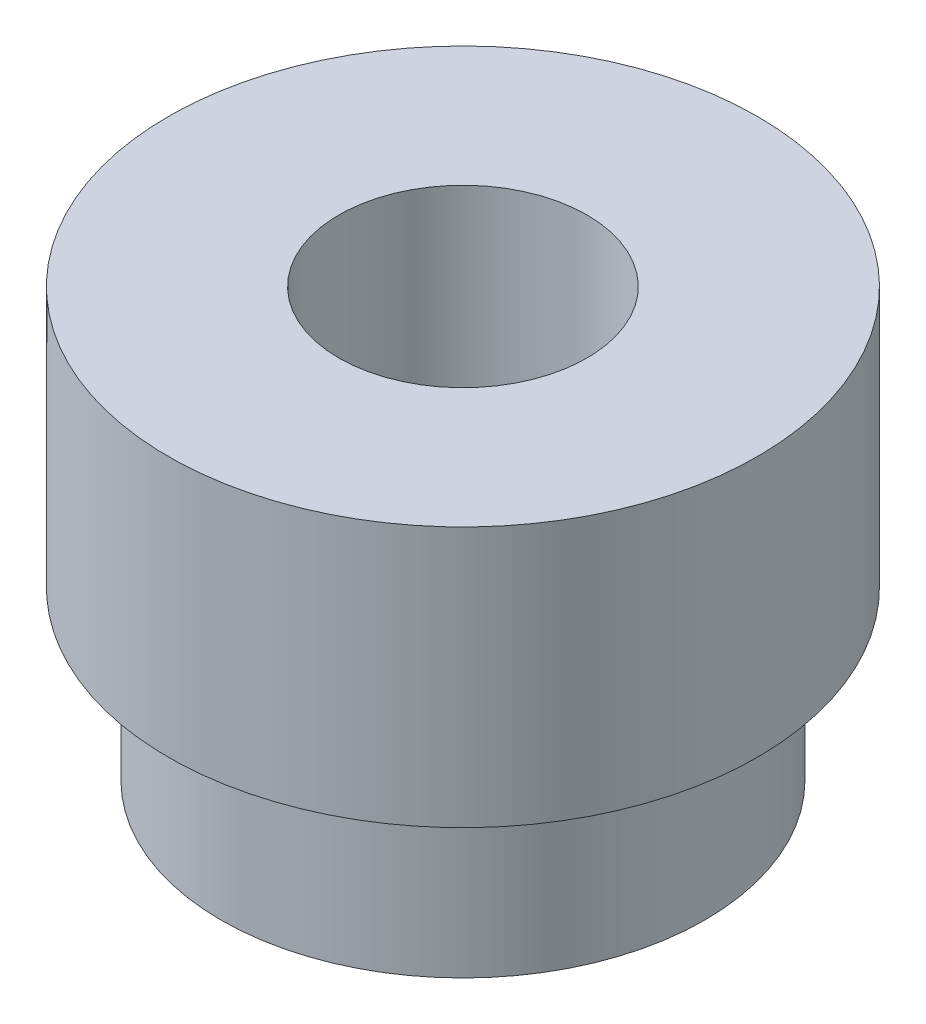
SolidWorks part; units mm, degrees
ref_plane "Front Plane" through (0, 0, 0) normal (0, 0, 1) x (1, 0, 0)
ref_plane "Top Plane" through (0, 0, 0) normal (0, 1, 0) x (1, 0, 0)
ref_plane "Right Plane" through (0, 0, 0) normal (1, 0, 0) x (0, 0, -1)
sketch "Sketch1" plane through (0, 0, 0) normal (0, 0, 1) x (1, 0, 0)
  line L0 (0, 0) -> (0, 54.5922) construction
  line L1 (-1, 0) -> (-1.95, 0)
  line L2 (-1, 3.45) -> (-2.375, 3.45)
  line L3 (55, 0) -> (-55, 0) construction
  line L5 (-2.375, 3.45) -> (-2.375, 1.35)
  line L6 (-1, 0) -> (-1, 3.45)
  line L7 (-2.375, 1.35) -> (-1.95, 1.35)
  line L8 (-1.95, 1.35) -> (-1.95, 0)
  dimension "D1" = 3.45
  dimension "D2" = 2.1
  dimension "D4" = 4.75
  dimension "D5" = 2
  dimension "D7" = 3.9
revolve "Revolve1" add sketch "Sketch1" angle 360 about L0
